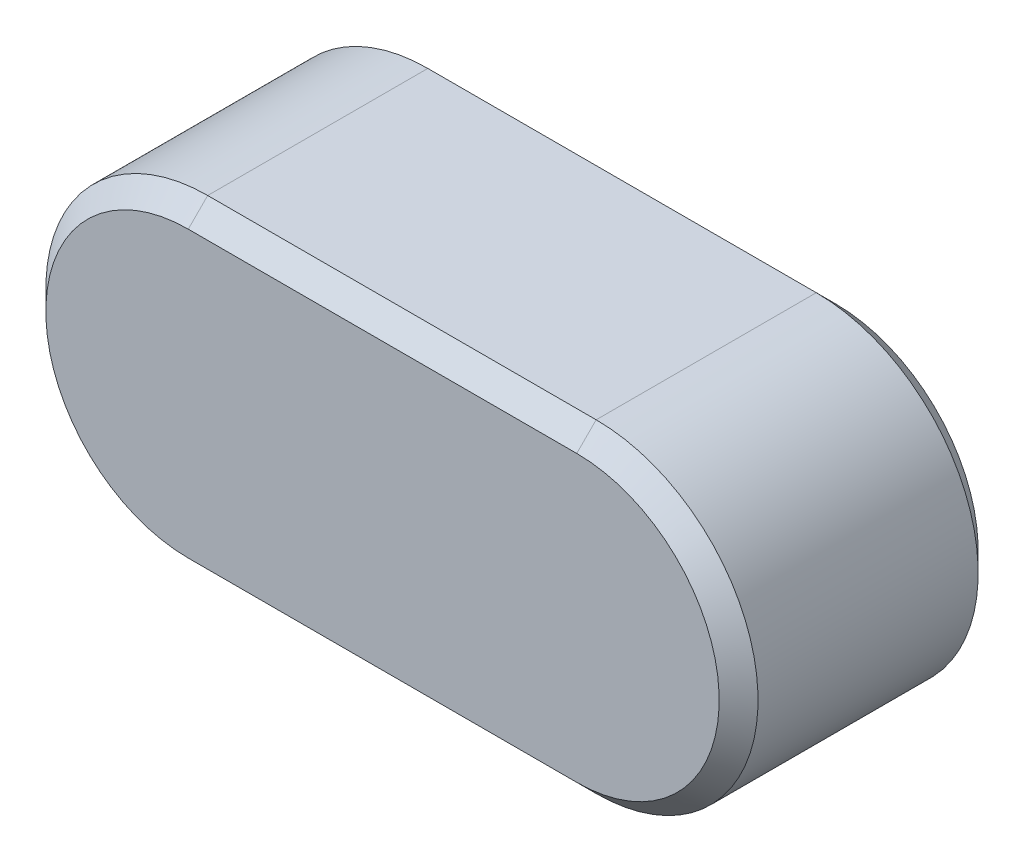
SolidWorks part; units mm, degrees
ref_plane "Front" through (0, 0, 0) normal (0, 0, 1) x (1, 0, 0)
ref_plane "Top" through (0, 0, 0) normal (0, 1, 0) x (1, 0, 0)
ref_plane "Right" through (0, 0, 0) normal (1, 0, 0) x (0, 0, -1)
sketch "Sketch1" plane through (0, 0, 0) normal (0, 0, 1) x (1, 0, 0)
  line L0 (-12, 5) -> (0, 5)
  line L1 (0, -5) -> (-12, -5)
  arc A0 (0, 5) -> (0, -5) centre (0, 0) cw
  arc A1 (-12, -5) -> (-12, 5) centre (-12, 0) cw
  dimension "L" = 22
  dimension "b" = 10
extrude "BaseKey" add sketch "Sketch1" along normal mid plane 8
sketch "Sketch2" plane through (0, 0, 0) normal (0, 0, 1) x (1, 0, 0)
  line L1 (-17, 5) -> (5, 5)
  line L2 (-17, 5) -> (-17, -5)
  line L3 (-17, -5) -> (5, -5)
  line L4 (5, 5) -> (5, -5)
  line L6 (0, -5) -> (-12, -5) construction
  line L7 (-12, 5) -> (0, 5) construction
  arc A2 (0, -5) -> (0, 5) centre (0, 0) ccw construction
  arc A3 (-12, 5) -> (-12, -5) centre (-12, 0) ccw construction
extrude "Extrude1" [suppressed] add sketch "Sketch2" along normal mid plane 8
sketch "Sketch3" plane through (0, 0, 0) normal (0, 0, 1) x (1, 0, 0)
  line L0 (5, 5) -> (-12, 5)
  line L1 (-12, -5) -> (5, -5)
  line L2 (5, -5) -> (5, 5)
  line L5 (-12, 5) -> (0, 5) construction
  arc A0 (-12, 5) -> (-12, -5) centre (-12, 0) ccw
  arc A1 (0, -5) -> (0, 5) centre (0, 0) ccw construction
  arc A4 (-12, 5) -> (-12, -5) centre (-12, 0) ccw construction
extrude "Extrude2" [suppressed] add sketch "Sketch3" along normal mid plane 8
chamfer "Chamfer1" distance 0.6 angle 45 8 edges at (5, 0, -4) (-6, -5, -4) (-17, 0, -4) (-6, 5, -4) (-17, 0, 4) (-6, -5, 4) (5, 0, 4) (-6, 5, 4)
equation "\"D1@Extrude1\"=\"h@BaseKey\""
equation "\"D1@Extrude2\"=\"h@BaseKey\""
